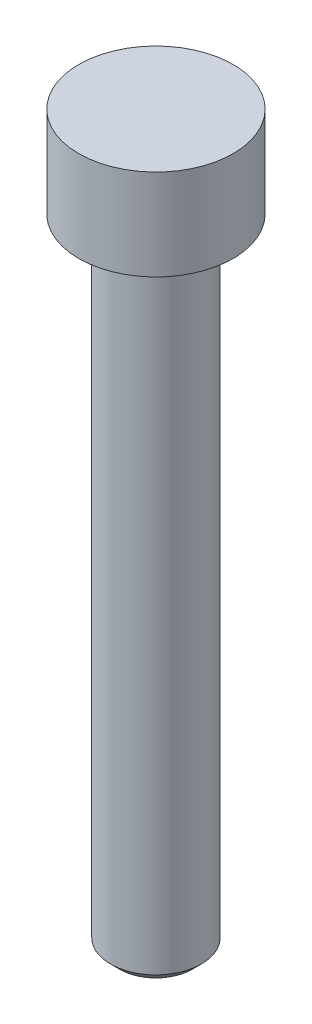
SolidWorks part; units mm, degrees
ref_plane "Front Plane" through (0, 0, 0) normal (0, 0, 1) x (1, 0, 0)
ref_plane "Top Plane" through (0, 0, 0) normal (0, 1, 0) x (1, 0, 0)
ref_plane "Right Plane" through (0, 0, 0) normal (1, 0, 0) x (0, 0, -1)
sketch "Sketch1" plane through (0, 0, 0) normal (0, 1, 0) x (1, 0, 0)
  circle A0 centre (0, 0) radius 4.25
  dimension "D1" = 8.5
extrude "Boss-Extrude1" add sketch "Sketch1" along normal blind 5
sketch "Sketch2" plane through (0, 0, 0) normal (0, -1, 0) x (1, 0, 0)
  circle A0 centre (0, 0) radius 2.5
  dimension "D1" = 5
extrude "Boss-Extrude2" add sketch "Sketch2" along normal blind 35
chamfer "Chamfer1" distance 0.5 angle 45 1 edges at (0, -35, -2.5)
